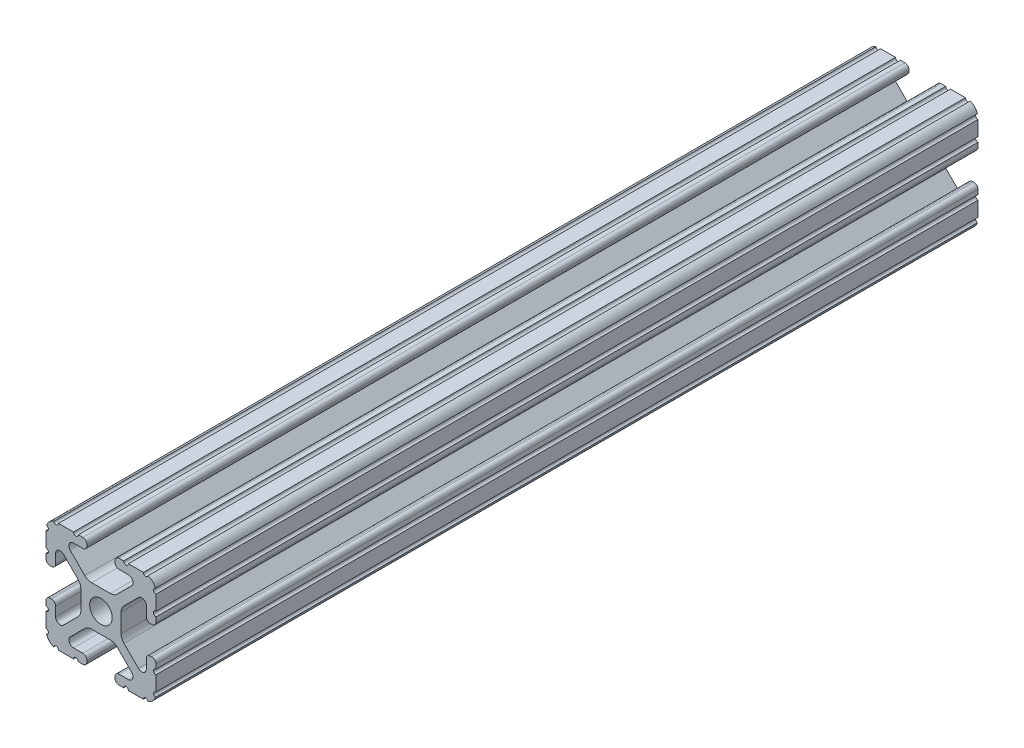
SolidWorks part; units mm, degrees
ref_plane "Front Plane" through (0, 0, 0) normal (0, 0, 1) x (1, 0, 0)
ref_plane "Top Plane" through (0, 0, 0) normal (0, 1, 0) x (1, 0, 0)
ref_plane "Right Plane" through (0, 0, 0) normal (1, 0, 0) x (0, 0, -1)
sketch "Sketch2" plane through (0, 0, 0) normal (0, 0, 1) x (1, 0, 0)
  line L0 (0, 12.7) -> (0, -12.7) construction
  line L1 (-12.7, 0) -> (12.7, 0) construction
  line L2 (3.2512, -12.7) -> (12.7, -12.7)
  line L3 (12.7, -12.7) -> (12.7, -3.2512)
  line L4 (3.2512, -12.7) -> (3.2512, -10.4902)
  line L5 (3.2512, -10.4902) -> (8.9276, -10.4902)
  line L6 (8.9276, -10.4902) -> (3.0856, -4.6482)
  line L7 (0, 0) -> (12.7, -12.7) construction
  line L8 (12.7, -3.2512) -> (10.4902, -3.2512)
  line L9 (10.4902, -3.2512) -> (10.4902, -8.9276)
  line L10 (10.4902, -8.9276) -> (4.6482, -3.0856)
  circle A0 centre (0, 0) radius 2.6035
  arc A1 (6.3485, -10.4902) -> (7.1039, -8.6665) centre (6.3485, -9.4219) ccw construction
  point P8 (0, -4.6482)
  dimension "Center Hole Diameter" = 5.207
  dimension "Rail Height" = 25.4
  dimension "Rail Width" = 25.4
  dimension "T-Slot Width" = 6.5024
  dimension "Slot Inner Width" = 14.8336
  dimension "Thickness" = 2.2098
  dimension "Slot Depth" = 5.842
  dimension "D1" = 2.2098
sketch "Sketch3" plane through (0, 0, 0) normal (1, 0, 0) x (0, 0, -1)
  line L0 (-94.9961, -12.7) -> (94.9961, -12.7) construction
  line L1 (-69.5961, 0) -> (69.5961, 0) construction
  line L4 (94.9961, 0) -> (-94.9961, 0) construction
sketch "Sketch4" plane through (0, 0, 0) normal (0, 0, 1) x (1, 0, 0)
  line L0 (4.1904, -12.7) -> (10.1173, -12.7)
  line L1 (3.2512, -12.7) -> (12.7, -12.7) construction
  line L2 (3.2512, -12.7) -> (3.2512, -10.4902) construction
  line L3 (3.2512, -10.4902) -> (8.9276, -10.4902) construction
  line L4 (3.2512, -11.4294) -> (3.2512, -11.7608)
  line L5 (4.1904, -10.4902) -> (6.3485, -10.4902)
  line L6 (0, -4.6482) -> (2.164, -4.6482)
  line L7 (8.9276, -10.4902) -> (3.0856, -4.6482) construction
  line L8 (3.7373, -5.2999) -> (7.1039, -8.6665)
  line L9 (12.7, -12.7) -> (12.7, -3.2512) construction
  line L10 (10.4902, -8.9276) -> (4.6482, -3.0856) construction
  line L11 (10.4902, -3.2512) -> (10.4902, -8.9276) construction
  line L12 (10.4902, -6.3485) -> (10.4902, -4.1904)
  line L13 (12.7, -3.2512) -> (10.4902, -3.2512) construction
  line L14 (11.4294, -3.2512) -> (11.7608, -3.2512)
  line L15 (12.7, -4.1904) -> (12.7, -10.1173)
  line L16 (8.6665, -7.1039) -> (5.2999, -3.7373)
  line L17 (4.6482, 0) -> (4.6482, -2.164)
  line L18 (-12.7, 0) -> (12.7, 0) construction
  line L19 (0, -4.6482) -> (0, -2.6035)
  line L20 (0, 12.7) -> (0, -12.7) construction
  line L21 (4.6482, 0) -> (2.6035, 0)
  arc A0 (3.2512, -11.7608) -> (4.1904, -12.7) centre (4.1904, -11.7608) ccw
  arc A2 (3.2512, -11.4294) -> (4.1904, -10.4902) centre (4.1904, -11.4294) cw
  arc A3 (6.3485, -10.4902) -> (7.1039, -8.6665) centre (6.3485, -9.4219) ccw
  arc A4 (2.164, -4.6482) -> (3.7373, -5.2999) centre (2.164, -6.8732) cw
  arc A5 (10.1173, -12.7) -> (12.7, -10.1173) centre (10.1173, -10.1173) ccw
  arc A6 (8.6665, -7.1039) -> (10.4902, -6.3485) centre (9.4219, -6.3485) ccw
  arc A7 (10.4902, -4.1904) -> (11.4294, -3.2512) centre (11.4294, -4.1904) cw
  arc A8 (11.7608, -3.2512) -> (12.7, -4.1904) centre (11.7608, -4.1904) cw
  arc A9 (5.2999, -3.7373) -> (4.6482, -2.164) centre (6.8732, -2.164) cw
  circle A10 centre (0, 0) radius 2.6035 construction
  arc A11 (0, -2.6035) -> (2.6035, 0) centre (0, 0) ccw
  dimension "D1" = 2.5827
  dimension "D2" = 2.225
  dimension "D3" = 0.9392
extrude "Boss-Extrude1" add sketch "Sketch4" along normal up to vertex (94.9961 mm away) from vertex at -94.9961 starting at point (0, -12.7, -94.9961)
sketch "Sketch5" plane through (0, 0, 0) normal (0, 0, 1) x (1, 0, 0)
  line L0 (3.2512, -12.7) -> (12.7, -12.7) construction
  line L1 (4.1904, -10.4902) -> (6.3485, -10.4902) construction
  line L3 (0, 0) -> (12.7, -12.7) construction
  line L4 (6.3485, -10.4902) -> (6.3485, -12.7) construction
  line L5 (8.9276, -10.4902) -> (3.0856, -4.6482) construction
  circle A0 centre (10.3562, -12.7) radius 0.5524
  circle A1 centre (5.796, -12.7) radius 0.5524
  circle A2 centre (12.7, -10.3562) radius 0.5524
  circle A3 centre (12.7, -5.796) radius 0.5524
  point P10 (5.2694, -10.4902)
  point P12 (9.4219, -6.3485)
  dimension "D1" = 1.1049
extrude "Cut-Extrude1" cut sketch "Sketch5" against normal through all both and the other way through all
mirror "Mirror1" about plane through (0, 0, 0) normal (1, 0, 0) of bodies 137 134
mirror "Mirror2" about plane through (0, 0, 0) normal (0, 1, 0) of bodies 135
equation "\"D1@Sketch2\"=\"Thickness@Sketch2\""
equation "\"D2@Sketch4\"=\"Slot Inner Width@Sketch2\"*0.15"
equation "\"D1@Sketch4\"=\"D3@Sketch4\"*2.75"
equation "\"D3@Sketch4\"=\"Thickness@Sketch2\"*0.425"
equation "\"D1@Sketch5\"=\"Thickness@Sketch2\"*0.5"
equation "\"D1@Boss-Extrude1\"=\"Length@Sketch3\""
